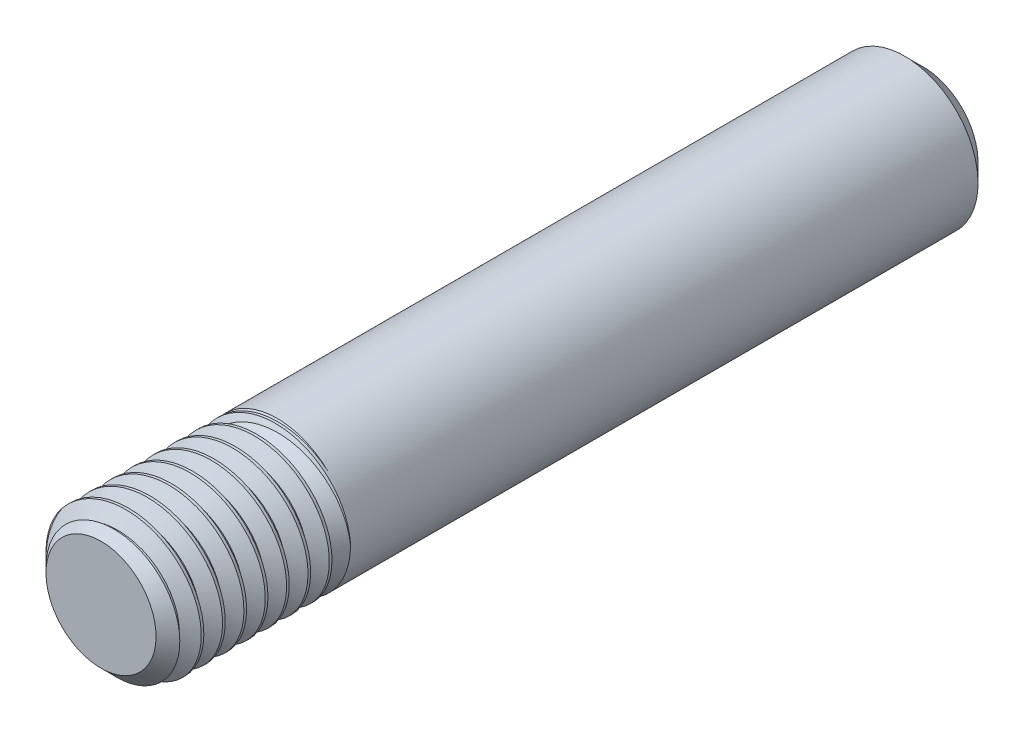
SolidWorks part; units mm, degrees
ref_plane "Front Plane" through (0, 0, 0) normal (0, 0, 1) x (1, 0, 0)
ref_plane "Top Plane" through (0, 0, 0) normal (0, 1, 0) x (1, 0, 0)
ref_plane "Right Plane" through (0, 0, 0) normal (1, 0, 0) x (0, 0, -1)
sketch "Sketch1" plane through (0, 0, 0) normal (1, 0, 0) x (0, 0, -1)
  line L0 (-44.45, 0) -> (44.45, 0) construction
  line L1 (44.45, 7.9375) -> (44.45, -7.9375) construction
  line L2 (-44.45, 7.9375) -> (-44.45, -7.9375) construction
  line L3 (-25.4, 7.9375) -> (-25.4, -7.9375) construction
  line L4 (-44.45, 7.9375) -> (-42.1409, 7.9375) construction
  line L5 (-44.45, -7.9375) -> (-38.6773, -7.9375) construction
  point P4 (44.45, 0)
  point P7 (-44.45, 0)
  point P8 (0, 0)
  point P11 (-25.4, 0)
  point P13 (-25.4, 0)
  point P17 (-38.6773, -7.9375)
  dimension "Length" = 88.9
  dimension "Thread Dia" = 15.875
  dimension "Shaft Dia" = 15.875
  dimension "Thread Length" = 19.05
  dimension "Shaft Length" = 69.85
  dimension "Pitch" = 2.3091
  dimension "D1" = 5.7727
sketch "Sketch2" plane through (0, 0, 0) normal (0, 0, 1) x (1, 0, 0)
  line L0 (-7.9375, 0) -> (7.9375, 0) construction
  line L1 (0, 7.9375) -> (0, -7.9375) construction
  circle A0 centre (0, 0) radius 7.9375 construction
  point P9 (0, 0)
  dimension "Shaft Dia" = 15.875
sketch "Sketch3" plane through (0, 0, 0) normal (1, 0, 0) x (0, 0, -1)
  line L0 (-44.45, 0) -> (44.45, 0)
  line L1 (44.45, 0) -> (44.45, 7.9375)
  line L2 (44.45, 7.9375) -> (-44.45, 7.9375) construction
  line L3 (-44.45, 7.9375) -> (-44.45, 0)
  line L4 (-44.45, 7.9375) -> (-25.4, 7.9375)
  line L5 (-25.4, 7.9375) -> (44.45, 7.9375)
revolve "Revolve1" add sketch "Sketch3" angle 360 about L0
chamfer "Chamfer1" distance 1.9844 angle 45 1 edges at (0, -7.9375, 44.45)
chamfer "Chamfer2" distance 1.9844 angle 45 1 edges at (0, -7.9375, -44.45)
ref_plane "Plane1" through (0, 0, 25.4) normal (0, 0, 1) x (1, 0, 0)
sketch "Sketch4" plane through (0, 0, 44.45) normal (0, 0, 1) x (1, 0, 0)
  circle A0 centre (0, 0) radius 7.9375
curve "Helix/Spiral1" pitch 2.3091 height 21.3591 turns 9.25
split "Split1" trim tools "Plane1" bodies to split 104 resulting bodies 105 106
sketch "Sketch5" plane through (0, 0, 0) normal (1, 0, 0) x (0, 0, -1)
  line L0 (-46.6148, 8.1875) -> (-44.3057, 8.1875) construction
  line L1 (-44.3057, 8.1875) -> (-45.4602, 6.1877) construction
  line L2 (-45.4602, 6.1877) -> (-46.6148, 8.1875) construction
  line L3 (-46.5426, 8.0625) -> (-44.3778, 8.0625) construction
  line L4 (-46.4705, 7.9375) -> (-44.45, 7.9375) construction
  line L5 (-45.6045, 6.4377) -> (-45.3159, 6.4377) construction
  line L6 (-45.4602, 6.4377) -> (-45.4602, 6.1877) construction
  line L7 (-45.4602, 7.9375) -> (-45.4602, 8.1875) construction
  line L8 (-46.5426, 8.0625) -> (-44.3778, 8.0625)
  line L9 (-44.3778, 8.0625) -> (-45.3159, 6.4377)
  line L10 (-45.3159, 6.4377) -> (-45.6045, 6.4377)
  line L11 (-45.6045, 6.4377) -> (-46.5426, 8.0625)
  point P12 (-45.4602, 8.0625)
  dimension "D1" = 2.3091
  dimension "D2" = 0.2886
sweep "Cut-Sweep1" cut profiles "Sketch5" path "Helix/Spiral1"
sketch "Sketch6" plane through (0, 0, 25.4) normal (0, 0, 1) x (1, 0, 0)
  circle A1 centre (0, 0) radius 7.9375
  circle A2 centre (0, 0) radius 7.9375
  dimension "D1" = 0
extrude "Boss-Extrude1" add sketch "Sketch6" along normal through all draft 30
equation "\"D1@Chamfer1\"=\"Thread Dia@Sketch1\"*.125"
equation "\"D1@Chamfer2\"=\"Shaft Dia@Sketch1\"*.125"
equation "\"D3@Helix/Spiral1\"=\"Thread Length@Sketch1\"+\"Pitch@Sketch1\""
equation "\"D4@Helix/Spiral1\"=\"Pitch@Sketch1\""
equation "\"D2@Sketch5\"=\"D1@Sketch5\"/8"
equation "\"D1@Sketch5\"=\"Pitch@Sketch1\""
equation "\"D1@Sketch1\"=\"Pitch@Sketch1\"*2.5"
